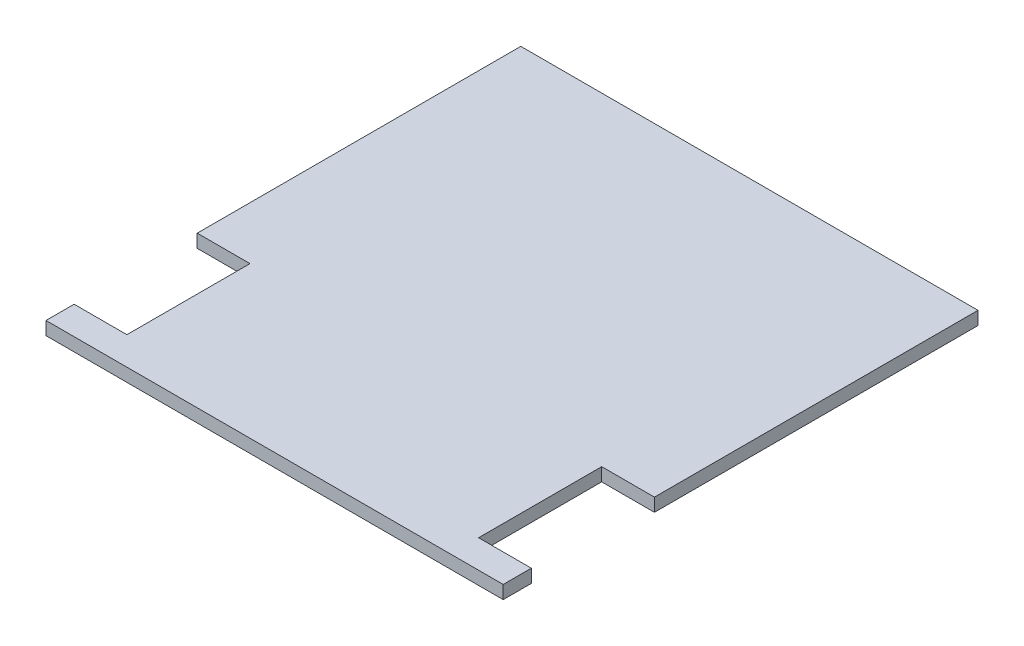
SolidWorks part; units mm, degrees
ref_plane "Front Plane" through (0, 0, 0) normal (0, 0, 1) x (1, 0, 0)
ref_plane "Top Plane" through (0, 0, 0) normal (0, 1, 0) x (1, 0, 0)
ref_plane "Right Plane" through (0, 0, 0) normal (1, 0, 0) x (0, 0, -1)
sketch "Sketch1" plane through (0, 0, 0) normal (0, 1, 0) x (1, 0, 0)
  line L0 (-19.3852, 35) -> (6.6148, 35)
  line L1 (-6.3852, 8) -> (-6.3852, 35) construction
  line L2 (6.6148, 35) -> (6.6148, 16.6)
  line L3 (6.6148, 16.6) -> (3.6148, 16.6)
  line L4 (3.6148, 16.6) -> (3.6148, 9.6)
  line L5 (3.6148, 9.6) -> (6.6148, 9.6)
  line L6 (6.6148, 9.6) -> (6.6148, 8)
  line L7 (6.6148, 8) -> (-19.3852, 8)
  line L8 (-19.3852, 9.6) -> (-19.3852, 8)
  line L9 (-16.3852, 9.6) -> (-19.3852, 9.6)
  line L10 (-16.3852, 16.6) -> (-16.3852, 9.6)
  line L11 (-19.3852, 16.6) -> (-16.3852, 16.6)
  line L12 (-19.3852, 35) -> (-19.3852, 16.6)
  point P4 (0, 0)
  point P8 (-6.3852, 35)
  dimension "D1" = 1.6
  dimension "D2" = 27
  dimension "D3" = 7
  dimension "D4" = 3
  dimension "D5" = 3
  dimension "D6" = 26
extrude "Boss-Extrude1" add sketch "Sketch1" along normal blind 0.75
